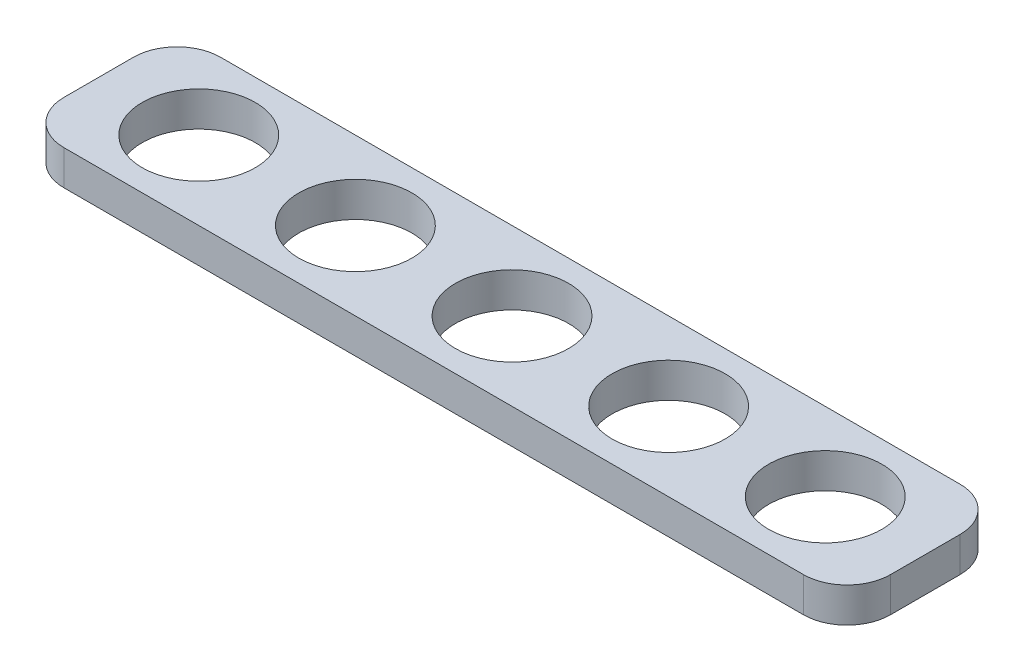
SolidWorks part; units mm, degrees
ref_plane "Front Plane" through (0, 0, 0) normal (0, 0, 1) x (1, 0, 0)
ref_plane "Top Plane" through (0, 0, 0) normal (0, 1, 0) x (1, 0, 0)
ref_plane "Right Plane" through (0, 0, 0) normal (1, 0, 0) x (0, 0, -1)
sketch "Sketch5" plane through (0, 0, 0) normal (0, 1, 0) x (1, 0, 0)
  line L1 (0, 0) -> (190, 0)
  line L2 (0, 0) -> (0, 36)
  line L3 (0, 36) -> (190, 36)
  line L4 (190, 0) -> (190, 36)
  dimension "D1" = 36
  dimension "D2" = 190
extrude "Boss-Extrude1" add sketch "Sketch5" along normal blind 8
sketch "Sketch6" plane through (0, 8, 0) normal (0, 1, 0) x (1, 0, 0)
  circle A0 centre (23, 18) radius 13
  circle A1 centre (59, 18) radius 13
  circle A2 centre (95.0046, 18) radius 13
  circle A3 centre (131.0046, 18) radius 13
  circle A4 centre (167.0023, 18) radius 12.9977
  point P6 (10, 18)
  point P7 (180, 18)
extrude "Cut-Extrude1" cut sketch "Sketch6" against normal blind 8
fillet "Fillet2" radius 10 4 edges at (190, 4, 0) (190, 4, -36) (0, 4, -36) (0, 4, 0)
